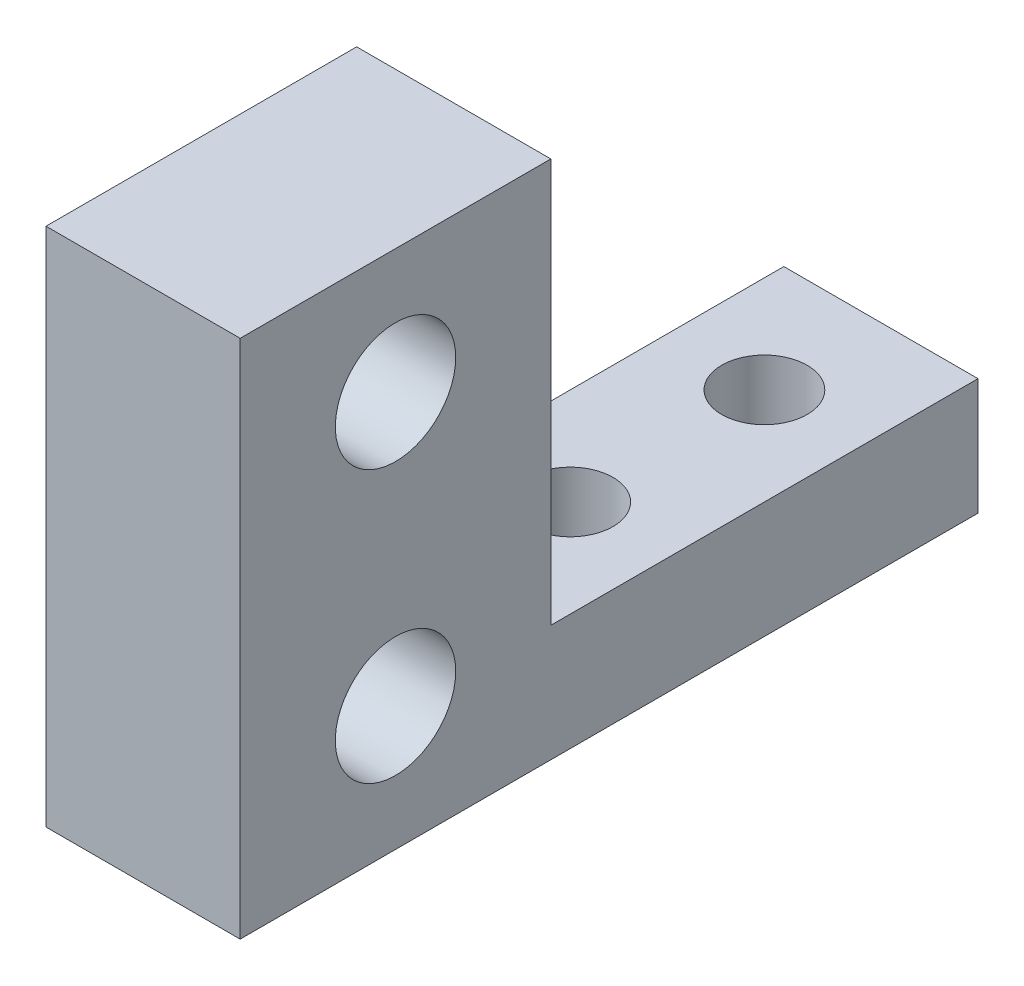
SolidWorks part; units mm, degrees
material "PLA"
ref_plane "前视基准面" through (0, 0, 0) normal (0, 0, 1) x (1, 0, 0)
ref_plane "上视基准面" through (0, 0, 0) normal (0, 1, 0) x (1, 0, 0)
ref_plane "右视基准面" through (0, 0, 0) normal (1, 0, 0) x (0, 0, -1)
sketch "草图1" plane through (0, 0, 0) normal (1, 0, 0) x (0, 0, -1)
  line L0 (-4, 10.2) -> (-4, -3.2)
  line L1 (-4, -3.2) -> (15, -3.2)
  line L2 (15, -3.2) -> (15, -0.2)
  line L3 (15, -0.2) -> (4, -0.2)
  line L4 (4, -0.2) -> (4, 10.2)
  line L5 (4, 10.2) -> (-4, 10.2)
  circle A0 centre (0, 0) radius 1.55
  circle A1 centre (0, 7) radius 1.55
  dimension "D2" = 3.1
  dimension "D1" = 7
  dimension "D3" = 3.2
  dimension "D4" = 3.2
  dimension "D5" = 4
  dimension "D6" = 8
  dimension "D7" = 3
  dimension "D8" = 11
extrude "凸台-拉伸1" add sketch "草图1" along normal blind 5
sketch "草图2" plane through (0, -0.2, 0) normal (0, 1, 0) x (1, 0, 0)
  line L0 (2.5, 4) -> (2.5, 10) construction
  line L1 (5, 4) -> (0, 4) construction
  circle A0 centre (2.5, 7) radius 1.1
  circle A1 centre (2.5, 12) radius 1.1
  dimension "D1" = 2.2
  dimension "D2" = 5
  dimension "D3" = 3
extrude "切除-拉伸1" cut sketch "草图2" against normal blind 5
